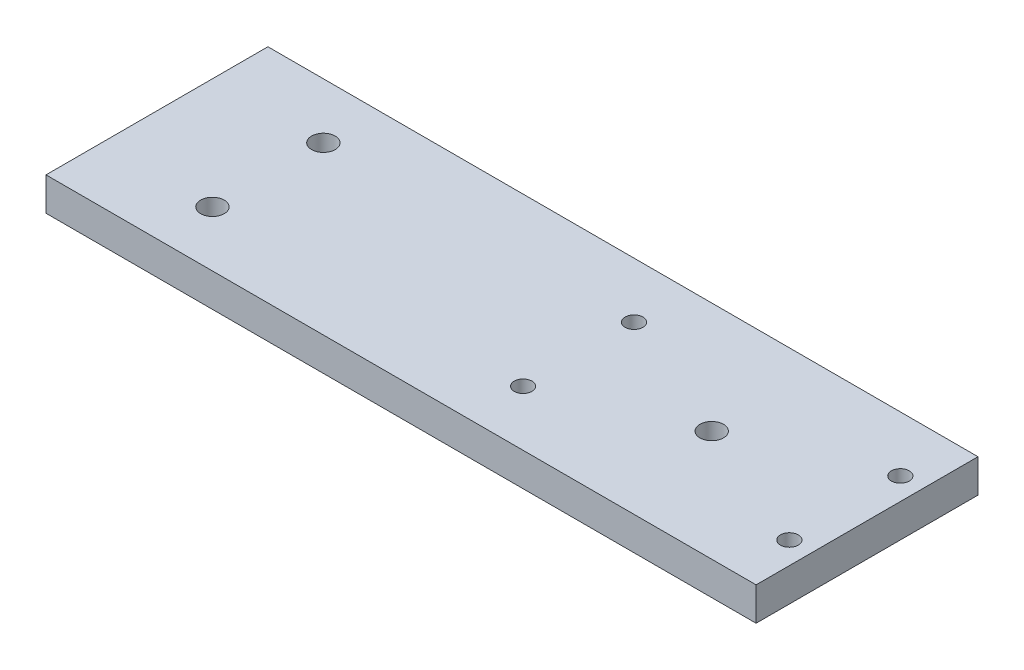
SolidWorks part; units mm, degrees
ref_plane "Front" through (0, 0, 0) normal (0, 0, 1) x (1, 0, 0)
ref_plane "Top" through (0, 0, 0) normal (0, 1, 0) x (1, 0, 0)
ref_plane "Right" through (0, 0, 0) normal (1, 0, 0) x (0, 0, -1)
sketch "Sketch1" plane through (0, 0, 0) normal (0, 1, 0) x (1, 0, 0)
  line L1 (-101.6, -31.75) -> (101.6, -31.75)
  line L2 (-101.6, -31.75) -> (-101.6, 31.75)
  line L3 (-101.6, 31.75) -> (101.6, 31.75)
  line L4 (101.6, -31.75) -> (101.6, 31.75)
  line L5 (-101.6, -31.75) -> (101.6, 31.75) construction
  line L6 (-101.6, 31.75) -> (101.6, -31.75) construction
  point P0 (0, 0)
  dimension "D1" = 203.2
  dimension "D2" = 63.5
extrude "Boss-Extrude1" add sketch "Sketch1" along normal blind 9.525 contours L3 L4 L1 L2
sketch "Sketch2" plane through (0, 0, 0) normal (0, -1, 0) x (1, 0, 0)
  point P0 (95.25, -15.875)
  point P1 (95.25, 15.875)
  point P3 (19.05, -15.875)
  point P5 (19.05, 15.875)
hole_wizard "#10 Clearance Hole1" positions "Sketch3" profile "Sketch5" hole size "#10" standard "ANSI Inch" end condition through all
sketch "Sketch3" plane through (0, 0, 0) normal (0, -1, 0) x (-1, 0, 0)
  point P0 (-19.05, 15.875)
  point P3 (-95.25, 15.875)
  point P6 (-95.25, -15.875)
  point P9 (-19.05, -15.875)
sketch "Sketch5" plane through (19.05, 0, -15.875) normal (1, 0, 0) x (0, 0, -1)
  line L0 (0, 0) -> (0, 9.525)
  line L1 (0, 9.525) -> (2.5527, 9.525)
  line L2 (2.5527, 9.525) -> (2.5527, 0)
  line L5 (2.5527, 0) -> (0, 0)
  line L11 (0, -6.35) -> (0, 107.95) construction
  dimension "Thru Hole Dia." = 5.1054
  dimension "Thru Hole Depth" = 9.525
sketch "Sketch6" plane through (0, 0, 0) normal (0, -1, 0) x (1, 0, 0)
  point P0 (57.15, 0)
hole_wizard "1/4 Clearance Hole1" positions "Sketch7" profile "Sketch8" hole size "1/4" standard "ANSI Inch" end condition through all
sketch "Sketch7" plane through (0, 0, 0) normal (0, -1, 0) x (-1, 0, 0)
  point P0 (-57.15, 0)
sketch "Sketch8" plane through (57.15, 0, 0) normal (1, 0, 0) x (0, 0, -1)
  line L0 (0, 0) -> (0, 9.525)
  line L1 (0, 9.525) -> (3.3782, 9.525)
  line L2 (3.3782, 9.525) -> (3.3782, 0)
  line L5 (3.3782, 0) -> (0, 0)
  line L11 (0, -6.35) -> (0, 107.95) construction
  dimension "Thru Hole Dia." = 6.7564
  dimension "Thru Hole Depth" = 9.525
sketch "Sketch9" plane through (0, 0, 0) normal (0, -1, 0) x (1, 0, 0)
  line L0 (-101.6, 31.75) -> (-101.6, -31.75) construction
  point P0 (-69.85, -15.875)
  point P1 (-69.85, 15.875)
  point P2 (0, 0)
  dimension "D1" = 31.75
hole_wizard "1/4 Clearance Hole2" positions "Sketch10" profile "Sketch11" hole size "1/4" standard "ANSI Inch" end condition through all
sketch "Sketch10" plane through (0, 0, 0) normal (0, -1, 0) x (-1, 0, 0)
  point P0 (69.85, 15.875)
  point P3 (69.85, -15.875)
sketch "Sketch11" plane through (-69.85, 0, -15.875) normal (1, 0, 0) x (0, 0, -1)
  line L0 (0, 0) -> (0, 9.525)
  line L1 (0, 9.525) -> (3.3782, 9.525)
  line L2 (3.3782, 9.525) -> (3.3782, 0)
  line L5 (3.3782, 0) -> (0, 0)
  line L11 (0, -6.35) -> (0, 107.95) construction
  dimension "Thru Hole Dia." = 6.7564
  dimension "Thru Hole Depth" = 9.525
